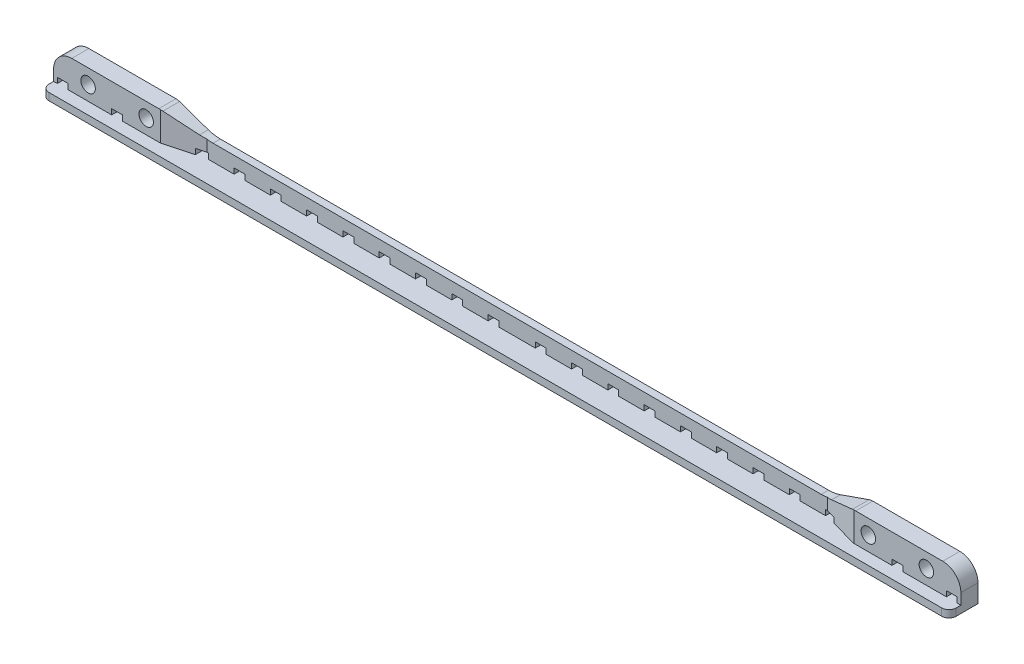
SolidWorks part; units mm, degrees
ref_plane "Front Plane" through (0, 0, 0) normal (0, 0, 1) x (1, 0, 0)
ref_plane "Top Plane" through (0, 0, 0) normal (0, 1, 0) x (1, 0, 0)
ref_plane "Right Plane" through (0, 0, 0) normal (1, 0, 0) x (0, 0, -1)
sketch "Sketch1" plane through (0, 0, 0) normal (1, 0, 0) x (0, 0, -1)
  line L0 (-3.2792, -8) -> (0, -8)
  line L1 (0, -8) -> (0, 0)
  line L2 (0, 0) -> (4.7208, 0)
  line L3 (4.7208, 0) -> (4.7208, -10)
  line L4 (4.7208, -10) -> (-3.2792, -10)
  line L5 (-3.2792, -10) -> (-3.2792, -8)
  line L6 (0, -7) -> (0, -1) construction
  line L7 (-1, 0) -> (-9, 0) construction
  dimension "D1" = 8
  dimension "D2" = 2
extrude "Boss-Extrude1" add sketch "Sketch1" against normal blind 125
sketch "Sketch2" plane through (0, -8, 0) normal (0, 1, 0) x (1, 0, 0)
  line L0 (-95.5, 0) -> (-85.5, 2.7208)
  line L1 (-125, 0) -> (0, 0) construction
  line L2 (-95.5, -1) -> (-95.5, 0) construction
  line L3 (-85.5, 2.7208) -> (0, 2.7208)
  line L4 (0, 4.7208) -> (0, 0) construction
  line L5 (-125, 4.7208) -> (0, 4.7208) construction
  line L6 (-95.5, 0) -> (0, 0)
  line L7 (0, 0) -> (0, 2.7208)
  dimension "D1" = 2
  dimension "D2" = 10
extrude "Cut-Extrude2" cut sketch "Sketch2" along normal through all
sketch "Sketch3" plane through (0, 0, -2.7208) normal (0, 0, 1) x (1, 0, 0)
  line L0 (-125, -8) -> (-95.5, -8) construction
  line L1 (-124, -8) -> (-121, -8)
  line L2 (-124, -8) -> (-124, -6.5)
  line L3 (-124, -6.5) -> (-121, -6.5)
  line L4 (-121, -8) -> (-121, -6.5)
  line L5 (-122.5, -6.5) -> (-122.5, -8) construction
  line L6 (-124, -7.25) -> (-121, -7.25) construction
  line L7 (-125, 0) -> (-125, -8) construction
  line L8 (-125, -8) -> (0, -8) construction
  line L9 (-5, -8) -> (-8, -8)
  line L10 (-5, -8) -> (-5, -6.5)
  line L11 (-5, -6.5) -> (-8, -6.5)
  line L12 (-8, -8) -> (-8, -6.5)
  line L13 (-6.5, -6.5) -> (-6.5, -8) construction
  line L14 (-5, -7.25) -> (-8, -7.25) construction
  line L15 (0, 0) -> (0, -8) construction
  line L16 (-15, -6.5) -> (-18, -6.5)
  line L17 (-18, -8) -> (-18, -6.5)
  line L18 (-15, -8) -> (-18, -8)
  line L19 (-15, -8) -> (-15, -6.5)
  line L20 (-25, -6.5) -> (-28, -6.5)
  line L21 (-28, -8) -> (-28, -6.5)
  line L22 (-25, -8) -> (-28, -8)
  line L23 (-25, -8) -> (-25, -6.5)
  line L24 (-35, -6.5) -> (-38, -6.5)
  line L25 (-38, -8) -> (-38, -6.5)
  line L26 (-35, -8) -> (-38, -8)
  line L27 (-35, -8) -> (-35, -6.5)
  line L28 (-45, -6.5) -> (-48, -6.5)
  line L29 (-48, -8) -> (-48, -6.5)
  line L30 (-45, -8) -> (-48, -8)
  line L31 (-45, -8) -> (-45, -6.5)
  line L32 (-55, -6.5) -> (-58, -6.5)
  line L33 (-58, -8) -> (-58, -6.5)
  line L34 (-55, -8) -> (-58, -8)
  line L35 (-55, -8) -> (-55, -6.5)
  line L36 (-65, -6.5) -> (-68, -6.5)
  line L37 (-68, -8) -> (-68, -6.5)
  line L38 (-65, -8) -> (-68, -8)
  line L39 (-65, -8) -> (-65, -6.5)
  line L40 (-75, -6.5) -> (-78, -6.5)
  line L41 (-78, -8) -> (-78, -6.5)
  line L42 (-75, -8) -> (-78, -8)
  line L43 (-75, -8) -> (-75, -6.5)
  line L44 (-85, -6.5) -> (-88, -6.5)
  line L45 (-88, -8) -> (-88, -6.5)
  line L46 (-85, -8) -> (-88, -8)
  line L47 (-85, -8) -> (-85, -6.5)
  line L48 (-107.5, -17) -> (-107.5, -8) construction
  line L49 (-109, -6.5) -> (-106, -6.5)
  line L50 (-109, -6.5) -> (-109, -8)
  line L51 (-109, -8) -> (-106, -8)
  line L52 (-106, -6.5) -> (-106, -8)
  line L53 (-107.5, -8) -> (-107.5, -6.5) construction
  line L54 (-109, -7.25) -> (-106, -7.25) construction
  line L55 (-95.5, -17) -> (-119.5, -17) construction
  point P56 (0, 0)
  point P120 (-122.5, -7.25)
  point P185 (-6.5, -7.25)
  point P234 (-107.5, -7.25)
  dimension "D1" = 1
  dimension "D2" = 3
  dimension "D3" = 1.5
  dimension "D4" = 5
  dimension "D5" = 9
extrude "Cut-Extrude3" cut sketch "Sketch3" against normal through all both and the other way through all
sketch "Sketch4" plane through (0, 0, -2.7208) normal (0, 0, 1) x (1, 0, 0)
  line L0 (0, -3.5) -> (-85.5, -3.5)
  line L1 (0, 0) -> (0, -8) construction
  line L2 (-85.5, 0) -> (-85.5, -6.5) construction
  line L3 (-85.5, -3.5) -> (-95.5, 0)
  line L4 (-45, -6.5) -> (-48, -6.5) construction
  dimension "D1" = 3
extrude "Cut-Extrude4" cut sketch "Sketch4" against normal through all and the other way through all flip side to cut
sketch "Sketch5" plane through (0, 0, -4.7208) normal (0, 0, -1) x (-1, 0, 0)
  circle A1 centre (99.5, -4) radius 2
  circle A2 centre (99.5, -4) radius 2
  circle A3 centre (115.5, -4) radius 2
  circle A4 centre (115.5, -4) radius 2
  dimension "D1" = 0
  dimension "D2" = 0
extrude "Cut-Extrude5" cut sketch "Sketch5" against normal through all
fillet "Fillet1" radius 5 1 edges at (-125, 0, -2.3604)
fillet "Fillet2" radius 3 1 edges at (-95.5, 0, -2.3604)
fillet "Fillet3" radius 10 1 edges at (-85.5, -3.5, -3.7208)
fillet "Fillet4" radius 2 1 edges at (-125, -9, 3.2792)
mirror "Mirror1" about plane through (0, 0, 0) normal (-1, 0, 0) of bodies 105
